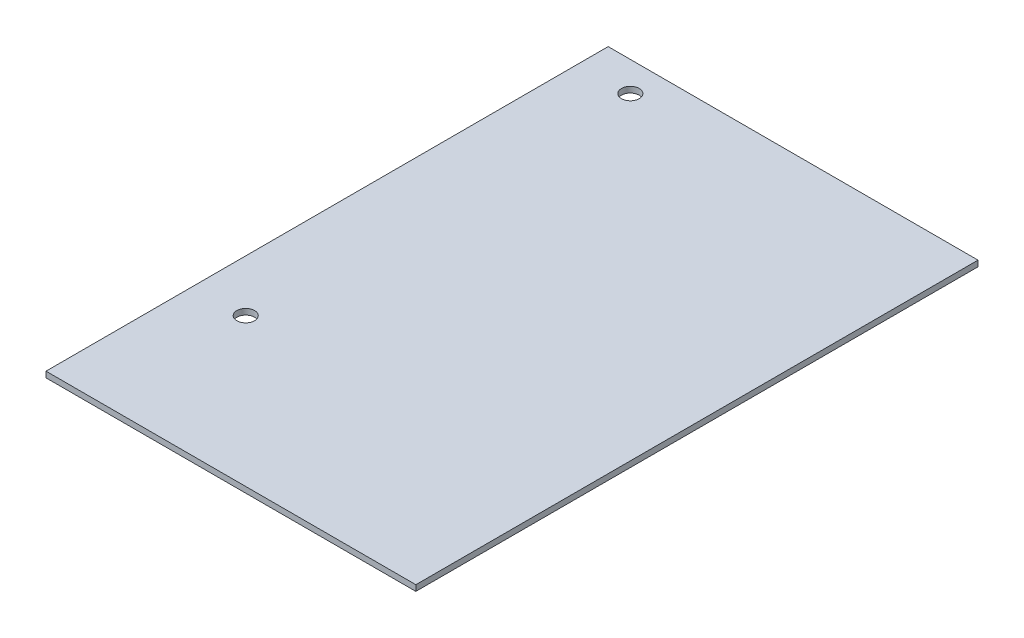
SolidWorks part; units mm, degrees
ref_plane "Front" through (0, 0, 0) normal (0, 0, 1) x (1, 0, 0)
ref_plane "Top" through (0, 0, 0) normal (0, 1, 0) x (1, 0, 0)
ref_plane "Right" through (0, 0, 0) normal (1, 0, 0) x (0, 0, -1)
sketch "Sketch1" plane through (0, 0, 0) normal (0, 1, 0) x (1, 0, 0)
  line L1 (0, 0) -> (63.5, 0)
  line L2 (0, 0) -> (0, 96.52)
  line L3 (0, 96.52) -> (63.5, 96.52)
  line L4 (63.5, 0) -> (63.5, 96.52)
  dimension "D1" = 63.5
  dimension "D2" = 96.52
extrude "Boss-Extrude1" add sketch "Sketch1" along normal blind 1
sketch "Sketch2" plane through (0, 1, 0) normal (0, 1, 0) x (1, 0, 0)
  line L0 (63.5, 96.52) -> (0, 96.52) construction
  line L2 (0, 96.52) -> (0, 0) construction
  circle A1 centre (8.89, 91.44) radius 1.524
  point P5 (8.89, 91.44)
  dimension "D3" = 5.08
  dimension "D4" = 8.89
extrude "mounting holes (1)" cut sketch "Sketch2" against normal blind 2
sketch "Sketch3" plane through (0, 1, 0) normal (0, 1, 0) x (1, 0, 0)
  line L1 (0, 0) -> (63.5, 0) construction
  line L3 (0, 96.52) -> (0, 0) construction
  circle A1 centre (8.89, 25.4) radius 1.524
  dimension "D3" = 25.4
  dimension "D4" = 8.89
extrude "mounting holes (2)" cut sketch "Sketch3" against normal blind 3
sketch "holding tab rectangle" plane through (0, 1, 0) normal (0, 1, 0) x (1, 0, 0)
  line L0 (63.5, 0) -> (63.5, 96.52) construction
  line L1 (63.5, 46.355) -> (60.325, 46.355)
  line L2 (63.5, 46.355) -> (63.5, 41.91)
  line L3 (63.5, 41.91) -> (60.325, 41.91)
  line L4 (60.325, 46.355) -> (60.325, 41.91)
  line L5 (63.5, 96.52) -> (0, 96.52) construction
  dimension "D1" = 50.165
sketch "Sketch4" plane through (0, 1, 0) normal (0, 1, 0) x (1, 0, 0)
  line L0 (63.5, 96.52) -> (0, 96.52) construction
  line L1 (0, 96.52) -> (0, 0) construction
  circle A0 centre (34.4805, 16.3017) radius 0.889
  dimension "D3" = 1.778
  dimension "D1" = 80.2183
  dimension "D2" = 34.4805
